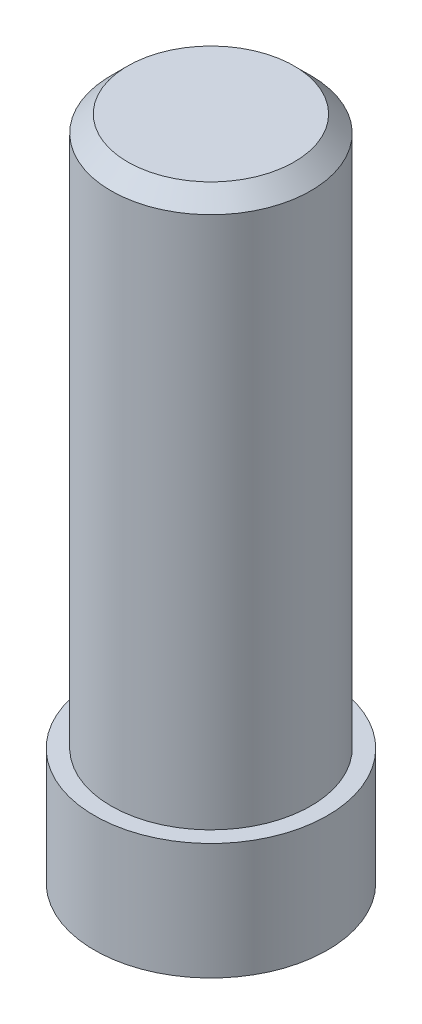
SolidWorks part; units mm, degrees
ref_plane "Front Plane" through (0, 0, 0) normal (0, 0, 1) x (1, 0, 0)
ref_plane "Top Plane" through (0, 0, 0) normal (0, 1, 0) x (1, 0, 0)
ref_plane "Right Plane" through (0, 0, 0) normal (1, 0, 0) x (0, 0, -1)
sketch "Sketch1" plane through (0, 0, 0) normal (0, 1, 0) x (1, 0, 0)
  circle A1 centre (0, 0) radius 6
  dimension "D1" = 12
extrude "Boss-Extrude2" add sketch "Sketch1" along normal mid plane 33
sketch "Sketch2" plane through (0, -16.5, 0) normal (0, -1, 0) x (1, 0, 0)
  circle A0 centre (0, 0) radius 7
  dimension "D1" = 14
extrude "Boss-Extrude3" add sketch "Sketch2" along normal blind 7
chamfer "Chamfer1" distance 1 angle 45 1 edges at (0, 16.5, 6)
